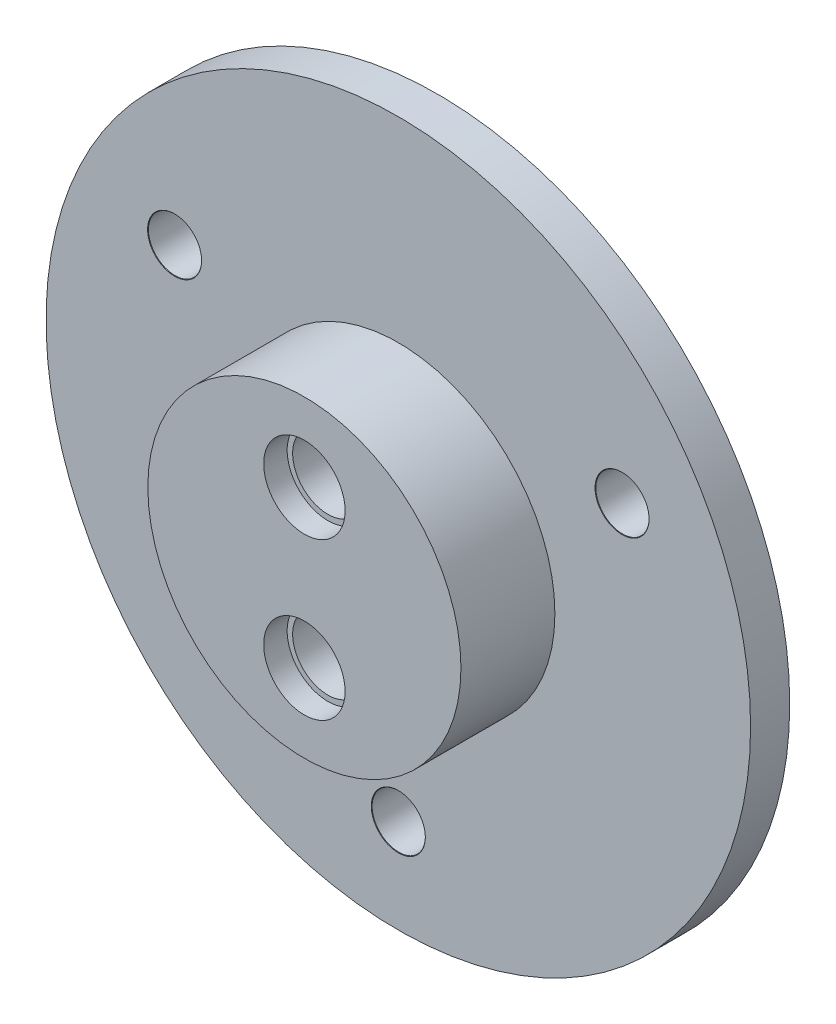
SolidWorks part; units mm, degrees
ref_plane "Front Plane" through (0, 0, 0) normal (0, 0, 1) x (1, 0, 0)
ref_plane "Top Plane" through (0, 0, 0) normal (0, 1, 0) x (1, 0, 0)
ref_plane "Right Plane" through (0, 0, 0) normal (1, 0, 0) x (0, 0, -1)
sketch "Sketch1" plane through (0, 0, 0) normal (0, 0, 1) x (1, 0, 0)
  circle A0 centre (0, 0) radius 22.5
  dimension "D1" = 45
extrude "Boss-Extrude1" add sketch "Sketch1" along normal blind 2.5
sketch "Sketch2" plane through (0, 0, 2.5) normal (0, 0, 1) x (1, 0, 0)
  line L0 (0, 0) -> (0, -16.5) construction
  line L1 (-14.2894, 8.25) -> (0, 0) construction
  line L2 (0, 0) -> (14.2894, 8.25) construction
  circle A0 centre (0, 0) radius 16.5 construction
  point P7 (-14.2894, 8.25)
  point P8 (14.2894, 8.25)
  point P9 (0, -16.5)
  dimension "D1" = 33
  dimension "D2" = 120
  dimension "D3" = 120
sketch "Sketch5" plane through (0, 0, 2.5) normal (0, 0, 1) x (1, 0, 0)
  point P0 (-14.2894, 8.25)
  point P3 (14.2894, 8.25)
  point P6 (0, -16.5)
hole_wizard "M3 Clearance Hole1" positions "Sketch5" profile "Sketch4" hole size "M3" standard "ANSI Metric" end condition up to next
sketch "Sketch4" plane through (-14.2894, 8.25, 2.5) normal (1, 0, 0) x (0, -1, 0)
  line L0 (0, 0) -> (0, 2.5)
  line L1 (0, 2.5) -> (1.7, 2.5)
  line L2 (1.7, 2.5) -> (1.7, 0.025)
  line L3 (1.7, 0.025) -> (1.725, 0)
  line L5 (1.725, 0) -> (0, 0)
  line L6 (-1.7, 0.025) -> (-1.725, 0) construction
  line L11 (0, -6.35) -> (0, 107.95) construction
  dimension "Thru Hole Dia." = 3.4
  dimension "Thru Hole Depth" = 2.5
  dimension "Near C'Sink Dia." = 3.45
  dimension "Near C'Sink Angle" = 90
sketch "Sketch6" plane through (0, 0, 2.5) normal (0, 0, 1) x (1, 0, 0)
  circle A0 centre (0, 0) radius 10
  dimension "D1" = 20
extrude "Boss-Extrude2" add sketch "Sketch6" along normal blind 6
sketch "Sketch12" plane through (0, 0, 8.5) normal (0, 0, 1) x (1, 0, 0)
  line L0 (0, 0) -> (0, -16.5) construction
  line L1 (0, 5) -> (0, -5) construction
  point P0 (0, 5)
  point P2 (0, -5)
  point P12 (0, 0)
  dimension "D1" = 10
hole_wizard "Hole2" positions "Sketch12" profile "Sketch11" legacy end condition through all
sketch "Sketch11" plane through (0, 5, 8.5) normal (1, 0, 0) x (0, -1, 0)
  line L0 (0, 0) -> (0, 8.5)
  line L1 (0, 8.5) -> (2.25, 8.5)
  line L2 (2.25, 8.5) -> (2.25, 1.5)
  line L3 (2.25, 1.5) -> (2.6, 1.5)
  line L4 (2.6, 1.5) -> (2.6, 0)
  line L5 (2.6, 0) -> (0, 0)
  line L6 (0, 110) -> (0, -10) construction
  dimension "Diameter" = 4.5
  dimension "Depth" = 8.5
  dimension "C-Bore Diameter" = 5.2
  dimension "C-Bore Depth" = 1.5
